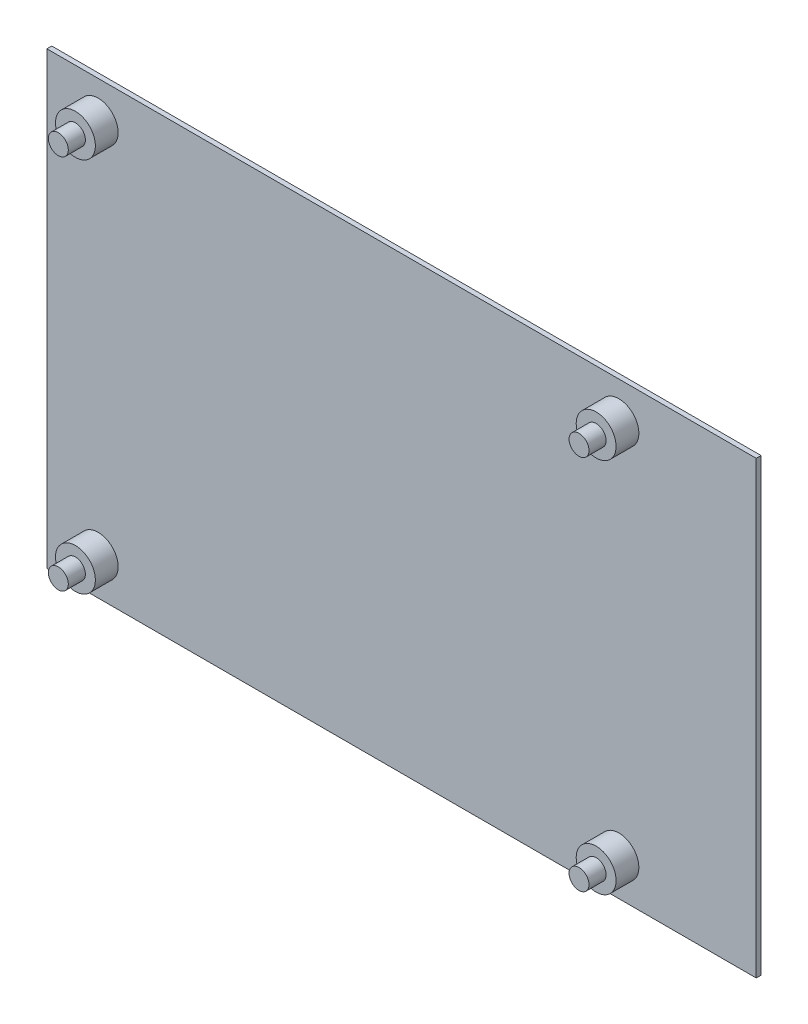
SolidWorks part; units mm, degrees
ref_plane "Front Plane" through (0, 0, 0) normal (0, 0, 1) x (1, 0, 0)
ref_plane "Top Plane" through (0, 0, 0) normal (0, 1, 0) x (1, 0, 0)
ref_plane "Right Plane" through (0, 0, 0) normal (1, 0, 0) x (0, 0, -1)
sketch "Sketch1" plane through (0, 0, 0) normal (0, 0, 1) x (1, 0, 0)
  line L0 (47.25, 21) -> (47.25, 22.7) construction
  line L1 (47.25, 22.7) -> (-77.25, 22.7)
  line L2 (47.25, 22.7) -> (47.25, -56.3)
  line L3 (47.25, -56.3) -> (-77.25, -56.3)
  line L4 (-77.25, 22.7) -> (-77.25, -56.3)
  line L5 (47.25, 22.7) -> (-77.25, -56.3) construction
  line L6 (47.25, -56.3) -> (-77.25, 22.7) construction
  point P0 (-15, -16.8)
  dimension "D1" = 79
extrude "Boss-Extrude1" add sketch "Sketch1" along normal blind 0.85
sketch "Sketch2" plane through (0, 0, 0.85) normal (0, 0, 1) x (1, 0, 0)
  line L1 (23.15, 16.2) -> (-68.25, 16.2) construction
  line L2 (23.15, 16.2) -> (23.15, -49.8) construction
  line L3 (23.15, -49.8) -> (-68.25, -49.8) construction
  line L4 (-68.25, 16.2) -> (-68.25, -49.8) construction
  line L5 (23.15, 16.2) -> (-68.25, -49.8) construction
  line L6 (23.15, -49.8) -> (-68.25, 16.2) construction
  line L7 (-77.25, 22.7) -> (-77.25, -56.3) construction
  line L8 (-49.3515, -49.8) -> (-49.3515, -56.3) construction
  line L9 (-77.25, -56.3) -> (47.25, -56.3) construction
  line L10 (-49.3515, 16.2) -> (-49.3515, 22.7) construction
  line L11 (47.25, 22.7) -> (-77.25, 22.7) construction
  circle A0 centre (-68.25, 16.2) radius 3.5
  circle A1 centre (23.15, 16.2) radius 3.5
  circle A2 centre (23.15, -49.8) radius 3.5
  circle A3 centre (-68.25, -49.8) radius 3.5
  point P0 (-22.55, -16.8)
  dimension "D4" = 7
  dimension "D1" = 91.4
  dimension "D2" = 66
  dimension "D3" = 9
extrude "Boss-Extrude2" add sketch "Sketch2" along normal blind 4
sketch "Sketch3" plane through (0, 0, 4.85) normal (0, 0, 1) x (1, 0, 0)
  circle A0 centre (-68.25, 16.2) radius 1.75
  circle A1 centre (23.15, 16.2) radius 1.75
  circle A2 centre (23.15, -49.8) radius 1.75
  circle A3 centre (-68.25, -49.8) radius 1.75
  dimension "D1" = 3.5
extrude "Boss-Extrude3" add sketch "Sketch3" along normal blind 3
